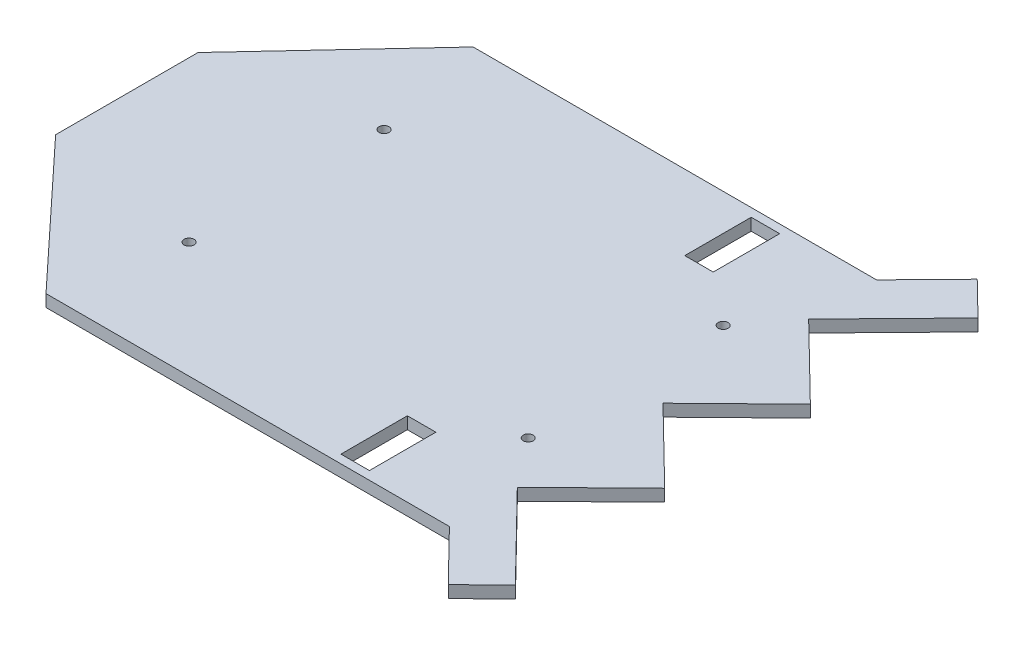
SolidWorks part; units mm, degrees
ref_plane "Front Plane" through (0, 0, 0) normal (0, 0, 1) x (1, 0, 0)
ref_plane "Top Plane" through (0, 0, 0) normal (0, 1, 0) x (1, 0, 0)
ref_plane "Right Plane" through (0, 0, 0) normal (1, 0, 0) x (0, 0, -1)
sketch "Sketch1" plane through (0, 0, 0) normal (0, 1, 0) x (1, 0, 0)
  line L8 (0, -30) -> (0, 30)
  line L16 (0, 30) -> (55.9448, 90)
  line L17 (55.9448, 90) -> (225.9448, 90)
  line L23 (-78.6671, 0) -> (289.3895, 0) construction
  line L27 (225.9448, -90) -> (246.9127, -111.4557)
  line L28 (246.9127, -111.4557) -> (261.2165, -97.4772)
  line L30 (261.2165, -97.4772) -> (225.9448, -61.3848)
  line L31 (225.9448, -61.3848) -> (257.3538, -30.69)
  line L41 (55.9448, -90) -> (225.9448, -90)
  line L42 (0, -30) -> (55.9448, -90)
  line L59 (257.3538, -30.69) -> (225.9448, 0)
  line L60 (257.3538, 30.69) -> (225.9448, 0)
  line L61 (225.9448, 61.3848) -> (257.3538, 30.69)
  line L62 (261.2165, 97.4772) -> (225.9448, 61.3848)
  line L63 (246.9127, 111.4557) -> (261.2165, 97.4772)
  line L64 (225.9448, 90) -> (246.9127, 111.4557)
  point P29 (0, 0)
  dimension "D1" = 30
  dimension "D2" = 90
  dimension "D3" = 170
  dimension "D4" = 170
  dimension "D5" = 170
  dimension "D6" = 20
  dimension "D7" = 30
  dimension "D8" = 43.9136
  dimension "D9" = 30.69
extrude "Boss-Extrude2" add sketch "Sketch1" along normal blind 5 and the other way blind 0.1
sketch "Sketch2" plane through (0, -0.1, 0) normal (0, -1, 0) x (1, 0, 0)
  line L0 (-25.4782, 0) -> (304.3329, 0) construction
  line L1 (57.3098, 76.812) -> (77.3098, 76.812)
  line L2 (57.3098, 76.812) -> (57.3098, 56.812)
  line L3 (57.3098, 56.812) -> (77.3098, 56.812)
  line L4 (77.3098, 76.812) -> (77.3098, 56.812)
  line L5 (77.3098, -76.812) -> (77.3098, -56.812)
  line L6 (57.3098, -56.812) -> (77.3098, -56.812)
  line L7 (57.3098, -76.812) -> (57.3098, -56.812)
  line L8 (57.3098, -76.812) -> (77.3098, -76.812)
  line L9 (220.2937, -76.812) -> (220.2937, -56.812)
  line L10 (220.2937, 76.812) -> (200.2937, 76.812)
  line L11 (220.2937, 76.812) -> (220.2937, 56.812)
  line L12 (220.2937, 56.812) -> (200.2937, 56.812)
  line L13 (200.2937, 76.812) -> (200.2937, 56.812)
  line L14 (220.2937, -56.812) -> (200.2937, -56.812)
  line L15 (200.2937, -76.812) -> (200.2937, -56.812)
  line L16 (220.2937, -76.812) -> (200.2937, -76.812)
  line L17 (188.6746, -58.4443) -> (176.6746, -58.4443)
  line L18 (188.6746, 86.4443) -> (176.6746, 86.4443)
  line L19 (188.6746, 86.4443) -> (188.6746, 58.4443)
  line L20 (188.6746, 58.4443) -> (176.6746, 58.4443)
  line L21 (176.6746, 86.4443) -> (176.6746, 58.4443)
  line L22 (188.6746, -86.4443) -> (188.6746, -58.4443)
  line L23 (176.6746, -86.4443) -> (176.6746, -58.4443)
  line L24 (188.6746, -86.4443) -> (176.6746, -86.4443)
  dimension "D1" = 20
  dimension "D2" = 20
  dimension "D3" = 20
  dimension "D4" = 20
  dimension "D5" = 28
  dimension "D6" = 12
sketch "Sketch4" plane through (0, -0.1, 0) normal (0, -1, 0) x (1, 0, 0)
  line L0 (57.3098, -76.812) -> (77.3098, -76.812) construction
  line L1 (77.3098, -76.812) -> (77.3098, -56.812) construction
  line L2 (220.2937, -76.812) -> (200.2937, -76.812) construction
  line L3 (220.2937, -76.812) -> (220.2937, -56.812) construction
  line L4 (-12.7915, 0) -> (315.7509, 0) construction
  line L5 (-25.4782, 0) -> (304.3329, 0) construction
  circle A0 centre (67.3098, -66.812) radius 2.1
  circle A1 centre (210.2937, -66.812) radius 2.1
  circle A2 centre (210.2937, 66.812) radius 2.1
  circle A3 centre (67.3098, 66.812) radius 2.1
  dimension "D1" = 4.2
  dimension "D2" = 10
  dimension "D3" = 10
  dimension "D4" = 4.2
  dimension "D5" = 10
  dimension "D6" = 10
sketch "Sketch5" plane through (0, -0.1, 0) normal (0, -1, 0) x (1, 0, 0)
  line L0 (-25.4782, 0) -> (304.3329, 0) construction
  circle A0 centre (33.3071, 0) radius 9
  circle A1 centre (33.3071, 20.75) radius 1.5
  circle A2 centre (33.3071, -20.75) radius 1.5
  dimension "D1" = 18
  dimension "D2" = 3
  dimension "D3" = 3
  dimension "D4" = 20.75
  dimension "D5" = 20.75
sketch "Sketch6" plane through (0, -0.1, 0) normal (0, -1, 0) x (-1, 0, 0)
  line L0 (-57.3098, 56.812) -> (-77.3098, 56.812) construction
  line L1 (-220.2937, 56.812) -> (-200.2937, 56.812) construction
  line L2 (25.4782, 0) -> (-315.7509, 0) construction
  circle A0 centre (-67.3098, 41.082) radius 2.1
  circle A1 centre (-210.2274, 41.082) radius 2.1
  circle A2 centre (-210.2274, -41.082) radius 2.1
  circle A3 centre (-67.3098, -41.082) radius 2.1
  dimension "D1" = 4.2
  dimension "D2" = 15.73
  dimension "D3" = 4.2
  dimension "D4" = 15.73
extrude "Cut-Extrude2" cut sketch "Sketch6" against normal blind 10
extrude "Cut-Extrude3" cut sketch "Sketch2" against normal blind 10 contours L19 L18 L21 L20 | L17 L23 L24 L22
sketch "Sketch8" plane through (0, -0.1, 0) normal (0, -1, 0) x (1, 0, 0)
  line L1 (140.7134, 53.2104) -> (174.7134, 53.2104)
  line L2 (140.7134, 53.2104) -> (140.7134, -52.7896)
  line L3 (140.7134, -52.7896) -> (174.7134, -52.7896)
  line L4 (174.7134, 53.2104) -> (174.7134, -52.7896)
  line L5 (81.08, 68.7059) -> (134.42, 68.7059)
  line L6 (81.08, 68.7059) -> (81.08, -0.0641)
  line L7 (81.08, -0.0641) -> (134.42, -0.0641)
  line L8 (134.42, 68.7059) -> (134.42, -0.0641)
  line L9 (85.1981, -26.9733) -> (128.1981, -26.9733)
  line L10 (85.1981, -26.9733) -> (85.1981, -69.9733)
  line L11 (85.1981, -69.9733) -> (128.1981, -69.9733)
  line L12 (128.1981, -26.9733) -> (128.1981, -69.9733)
  dimension "D1" = 106
  dimension "D2" = 34
  dimension "D3" = 43
  dimension "D4" = 43
  dimension "D5" = 68.77
  dimension "D6" = 53.34
